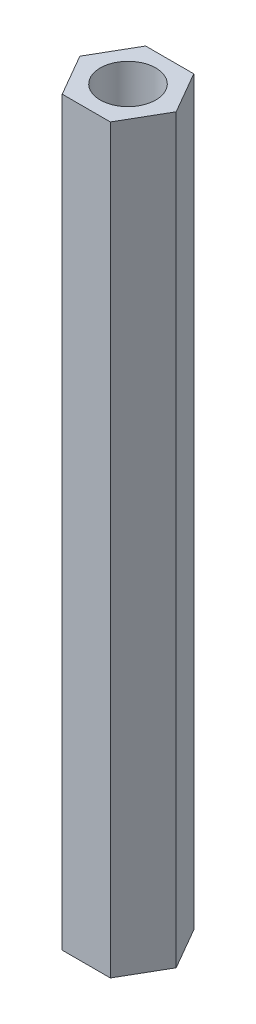
SolidWorks part; units mm, degrees
material "铝青铜"
ref_plane "前视基准面" through (0, 0, 0) normal (0, 0, 1) x (1, 0, 0)
ref_plane "上视基准面" through (0, 0, 0) normal (0, 1, 0) x (1, 0, 0)
ref_plane "右视基准面" through (0, 0, 0) normal (1, 0, 0) x (0, 0, -1)
sketch "草图1" plane through (0, 0, 0) normal (0, 1, 0) x (1, 0, 0)
  line L1 (2.5981, 0) -> (1.299, 2.25)
  line L2 (1.299, 2.25) -> (-1.299, 2.25)
  line L3 (-1.299, 2.25) -> (-2.5981, 0)
  line L4 (-2.5981, 0) -> (-1.299, -2.25)
  line L5 (-1.299, -2.25) -> (1.299, -2.25)
  line L6 (1.299, -2.25) -> (2.5981, 0)
  circle A0 centre (0, 0) radius 2.25 construction
  circle A1 centre (0, 0) radius 1.5
  dimension "D2" = 3
  dimension "D1" = 4.5
extrude "凸台-拉伸1" add sketch "草图1" along normal blind 40
